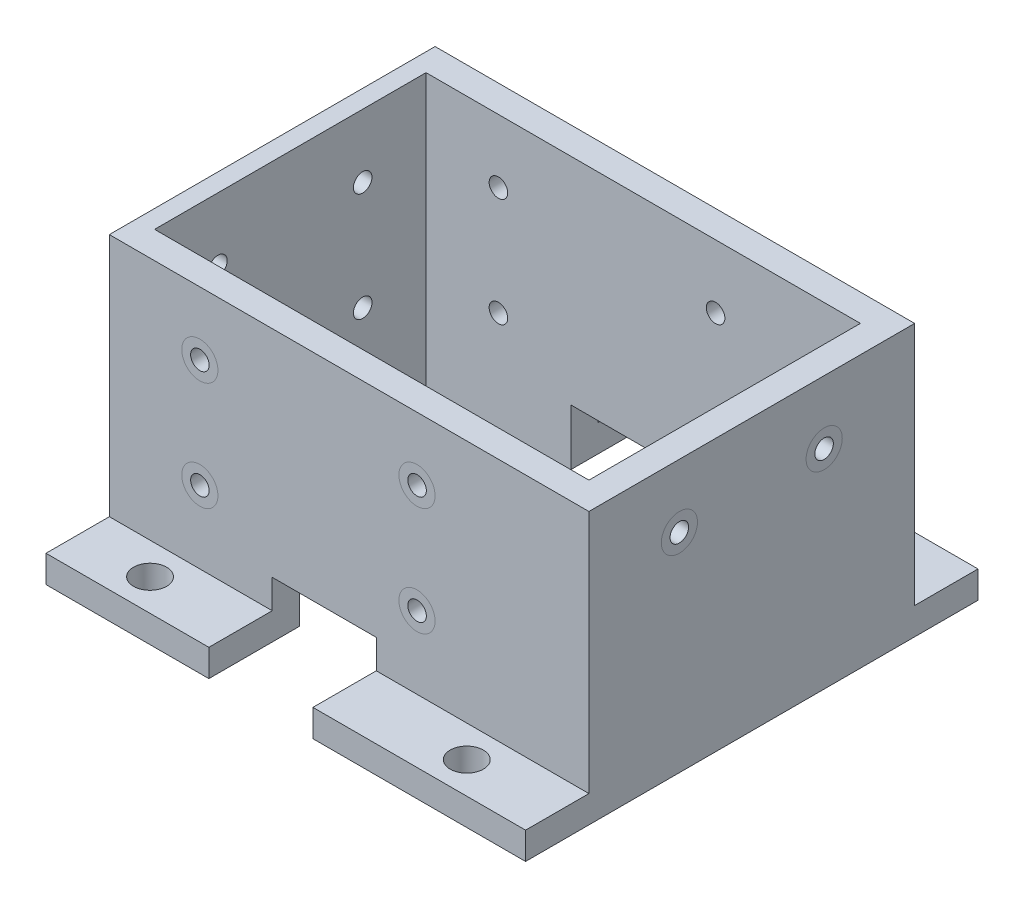
SolidWorks part; units mm, degrees
material "ABS"
ref_plane "Front Plane" through (0, 0, 0) normal (0, 0, 1) x (1, 0, 0)
ref_plane "Top Plane" through (0, 0, 0) normal (0, 1, 0) x (1, 0, 0)
ref_plane "Right Plane" through (0, 0, 0) normal (1, 0, 0) x (0, 0, -1)
sketch "Sketch1" plane through (0, 0, 0) normal (1, 0, 0) x (0, 0, -1)
  line L0 (0, 0) -> (0, 38)
  line L1 (0, 38) -> (36, 38)
  line L2 (36, 38) -> (36, 0)
  line L3 (36, 0) -> (0, 0)
  dimension "D1" = 38
  dimension "D2" = 36
extrude "Boss-Extrude2" add sketch "Sketch1" along normal blind 53
sketch "Sketch3" plane through (53, 0, 0) normal (1, 0, 0) x (0, 0, -1)
  line L0 (36, 0) -> (0, 0) construction
  line L1 (3, 0) -> (3, 35)
  line L2 (3, 35) -> (33, 35)
  line L3 (33, 35) -> (33, 0)
  line L4 (33, 0) -> (3, 0)
  line L5 (0, 38) -> (36, 38) construction
  line L6 (36, 38) -> (36, 0) construction
  line L7 (0, 0) -> (0, 38) construction
  dimension "D1" = 3
  dimension "D2" = 3
  dimension "D3" = 3
extrude "Cut-Extrude1" cut sketch "Sketch3" against normal blind 51
sketch "Sketch4" plane through (0, 0, 0) normal (0, 0, 1) x (1, 0, 0)
  line L0 (50, 0) -> (50, 30)
  line L1 (53, 0) -> (0, 0) construction
  line L2 (50, 30) -> (53, 30)
  line L3 (53, 38) -> (53, 0) construction
  line L4 (53, 30) -> (53, 0)
  line L5 (53, 0) -> (50, 0)
  dimension "D1" = 3
  dimension "D2" = 30
extrude "Boss-Extrude3" add sketch "Sketch4" against normal up to surface (33 mm away) up to face at (27.5, 17.5, -33)
sketch "Sketch5" plane through (0, 0, 0) normal (0, 0, 1) x (1, 0, 0)
  line L0 (53, 30) -> (0, 30)
  line L1 (53, 38) -> (53, 0) construction
  line L2 (0, 30) -> (0, 38)
  line L3 (53, 38) -> (0, 38) construction
  line L4 (0, 38) -> (53, 38)
  line L5 (53, 38) -> (53, 30)
  line L6 (53, 0) -> (0, 0) construction
  line L7 (0, 38) -> (0, 0) construction
  dimension "D1" = 30
  dimension "D2" = 0
extrude "Cut-Extrude2" cut sketch "Sketch5" against normal blind 52
sketch "Sketch6" plane through (0, 0, 0) normal (0, -1, 0) x (-1, 0, 0)
  line L0 (-53, 0) -> (-53, -7)
  line L1 (-53, -7) -> (0, -7)
  line L2 (0, -7) -> (0, 0)
  line L3 (0, 0) -> (-53, 0)
  line L4 (-53, 36) -> (-53, 43)
  line L5 (-53, 43) -> (0, 43)
  line L6 (0, 43) -> (0, 36)
  line L7 (0, 36) -> (-53, 36)
  dimension "D1" = 7
  dimension "D2" = 7
extrude "Boss-Extrude4" add sketch "Sketch6" against normal blind 3
sketch "Sketch8" plane through (0, 0, -43) normal (0, 0, -1) x (-1, 0, 0)
  line L0 (-29.5, 0) -> (-29.5, 3)
  line L1 (0, 0) -> (-53, 0) construction
  line L2 (-53, 3) -> (0, 3) construction
  line L3 (-29.5, 3) -> (-18, 3)
  line L4 (0, 3) -> (-53, 3) construction
  line L5 (-18, 3) -> (-18, 0)
  line L6 (-18, 0) -> (-29.5, 0)
  line L7 (-53, 3) -> (-53, 0) construction
  line L8 (0, 38) -> (0, 0) construction
  dimension "D1" = 23.5
  dimension "D2" = 18
extrude "Cut-Extrude4" cut sketch "Sketch8" against normal through all both and the other way through all
hole_wizard "M2.5 Tapped Hole13" positions "Sketch38" profile "Sketch35" tap size "M2.5" standard "AS"
sketch "Sketch38" plane through (0, 0, 0) normal (0, 0, 1) x (1, 0, 0)
  line L0 (0, 30) -> (0, 3) construction
  line L1 (18, 0) -> (0, 0) construction
  point P0 (10, 23)
  dimension "D1" = 10
  dimension "D2" = 23
sketch "Sketch35" plane through (10, 23, 0) normal (1, 0, 0) x (0, -1, 0)
  line L0 (0, 0) -> (0, 3)
  line L1 (0, 3) -> (1.025, 3)
  line L2 (1.025, 3) -> (1.025, 0.0085)
  line L3 (1.025, 0.0085) -> (2, 0)
  line L5 (2, 0) -> (0, 0)
  line L6 (-1.025, 0.0085) -> (-2, 0) construction
  line L11 (0, -6.35) -> (0, 107.95) construction
  dimension "Thru Tap Drill Dia." = 2.05
  dimension "Thru Tap Drill Depth" = 3
  dimension "Near C'Sink Dia." = 4
  dimension "Near C'Sink Angle" = 179
cosmetic thread "Hole Thread2" parameters "D2"=2.5
pattern_linear "LPattern1" count 2 spacing 24 along (1, 0, 0) count 2 spacing 12 along (0, -1, 0) of "M2.5 Tapped Hole13"
hole_wizard "M2.5 Tapped Hole14" positions "Sketch39" profile "Sketch40" tap size "M2.5" standard "AS"
sketch "Sketch39" plane through (0, 0, 0) normal (-1, 0, 0) x (0, 0, 1)
  line L0 (-36, 30) -> (0, 30) construction
  line L1 (-36, 3) -> (-36, 30) construction
  point P0 (-26, 23)
  dimension "D1" = 7
  dimension "D2" = 10
sketch "Sketch40" plane through (0, 23, -26) normal (0, 1, 0) x (0, 0, 1)
  line L0 (0, 0) -> (0, 2)
  line L1 (0, 2) -> (1.025, 2)
  line L2 (1.025, 2) -> (1.025, 0.0085)
  line L3 (1.025, 0.0085) -> (2, 0)
  line L5 (2, 0) -> (0, 0)
  line L6 (-1.025, 0.0085) -> (-2, 0) construction
  line L11 (0, -6.35) -> (0, 107.95) construction
  dimension "Thru Tap Drill Dia." = 2.05
  dimension "Thru Tap Drill Depth" = 2
  dimension "Near C'Sink Dia." = 4
  dimension "Near C'Sink Angle" = 179
cosmetic thread "Hole Thread3" parameters "D2"=2.5
pattern_linear "LPattern2" count 2 spacing 16 along (0, 0, 1) count 2 spacing 12 along (0, -1, 0) of "M2.5 Tapped Hole14"
hole_wizard "M2.5 Tapped Hole15" positions "Sketch41" profile "Sketch42" tap size "M2.5" standard "AS" end condition up to next
sketch "Sketch41" plane through (53, 0, 0) normal (1, 0, 0) x (0, 0, -1)
  line L0 (36, 30) -> (0, 30) construction
  line L1 (36, 3) -> (36, 30) construction
  point P0 (26, 23)
  dimension "D1" = 7
  dimension "D2" = 10
sketch "Sketch42" plane through (53, 23, -26) normal (0, 1, 0) x (0, 0, -1)
  line L0 (0, 0) -> (0, 3)
  line L1 (0, 3) -> (1.025, 3)
  line L2 (1.025, 3) -> (1.025, 0.0085)
  line L3 (1.025, 0.0085) -> (2, 0)
  line L5 (2, 0) -> (0, 0)
  line L6 (-1.025, 0.0085) -> (-2, 0) construction
  line L11 (0, -6.35) -> (0, 107.95) construction
  dimension "Thru Tap Drill Dia." = 2.05
  dimension "Thru Tap Drill Depth" = 3
  dimension "Near C'Sink Dia." = 4
  dimension "Near C'Sink Angle" = 179
cosmetic thread "Hole Thread4" parameters "D2"=2.5
pattern_linear "LPattern3" count 2 spacing 16 along (0, 0, 1) of "M2.5 Tapped Hole15"
hole_wizard "M2.5 Tapped Hole16" positions "Sketch43" profile "Sketch44" tap size "M2.5" standard "AS" end condition up to next
sketch "Sketch43" plane through (0, 0, -36) normal (0, 0, -1) x (-1, 0, 0)
  line L0 (0, 30) -> (-53, 30) construction
  line L1 (0, 3) -> (0, 30) construction
  point P0 (-10, 23)
  dimension "D1" = 7
  dimension "D2" = 10
sketch "Sketch44" plane through (10, 23, -36) normal (1, 0, 0) x (0, 1, 0)
  line L0 (0, 0) -> (0, 3)
  line L1 (0, 3) -> (1.025, 3)
  line L2 (1.025, 3) -> (1.025, 0.0085)
  line L3 (1.025, 0.0085) -> (2, 0)
  line L5 (2, 0) -> (0, 0)
  line L6 (-1.025, 0.0085) -> (-2, 0) construction
  line L11 (0, -6.35) -> (0, 107.95) construction
  dimension "Thru Tap Drill Dia." = 2.05
  dimension "Thru Tap Drill Depth" = 3
  dimension "Near C'Sink Dia." = 4
  dimension "Near C'Sink Angle" = 179
cosmetic thread "Hole Thread5" parameters "D2"=2.5
pattern_linear "LPattern4" count 2 spacing 24 along (1, 0, 0) count 2 spacing 12 along (0, -1, 0) of "M2.5 Tapped Hole16"
sketch "Sketch45" plane through (0, 3, 0) normal (0, 1, 0) x (1, 0, 0)
  line L0 (0, 36) -> (53, 36) construction
  line L1 (18, 43) -> (18, 36) construction
  circle A0 centre (8, 39.5) radius 1.8333
  dimension "D1" = 3.6667
  dimension "D2" = 3.5
  dimension "D3" = 10
extrude "Cut-Extrude5" cut sketch "Sketch45" against normal through all both and the other way through all
pattern_linear "LPattern5" count 2 spacing 35 along (1, 0, 0) count 2 spacing 43 along (0, 0, 1) of "Cut-Extrude5"
sketch "Sketch46" plane through (0, 0, -36) normal (0, 0, -1) x (-1, 0, 0)
  line L0 (-29.5, 3) -> (-29.5, 6.2)
  line L1 (-29.5, 6.2) -> (-18, 6.2)
  line L2 (-18, 6.2) -> (-18, 3)
  line L3 (-29.5, 3) -> (-18, 3)
  dimension "D1" = 3.2
extrude "Cut-Extrude6" cut sketch "Sketch46" against normal through all both and the other way through all
